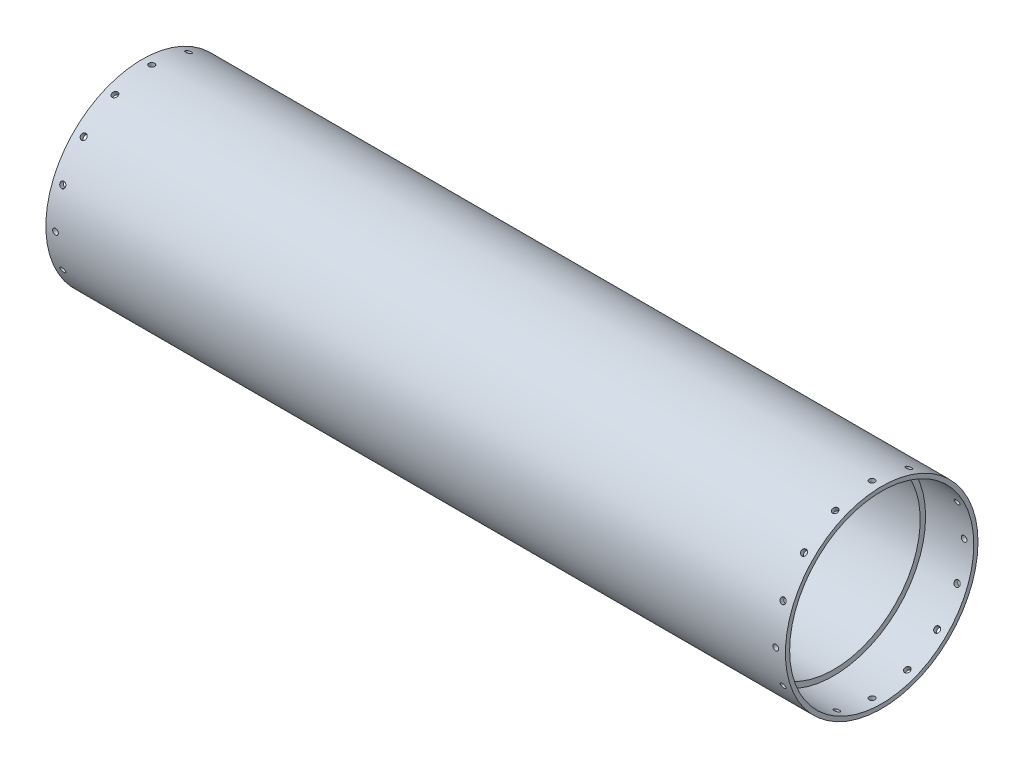
SolidWorks part; units mm, degrees
material "6061 Alloy"
ref_plane "Front Plane" through (0, 0, 0) normal (0, 0, 1) x (1, 0, 0)
ref_plane "Top Plane" through (0, 0, 0) normal (0, 1, 0) x (1, 0, 0)
ref_plane "Right Plane" through (0, 0, 0) normal (1, 0, 0) x (0, 0, -1)
sketch "Sketch1" plane through (0, 0, 0) normal (1, 0, 0) x (0, 0, -1)
  circle A0 centre (0, 0) radius 63.5
  circle A1 centre (0, 0) radius 57.15
  dimension "D1" = 127
  dimension "D2" = 6.35
extrude "Boss-Extrude1" add sketch "Sketch1" along normal blind 487.68
hole_wizard "#6 Clearance Hole1" positions "3DSketch2" profile "Sketch4" hole size "#6" standard "ANSI Inch"
sketch3d "3DSketch2"
  line L2 (6.35, 63.5, 0) -> (0, 63.5, 0) construction
  line L4 (0, 0, 0) -> (0, 63.5, 0) construction
  line L6 (6.35, 63.5, 0) -> (481.33, 63.5, 0) construction
  circle A0 centre (0, 0, 0) radius 63.5 construction
  point P0 (6.35, 63.5, 0)
  point P2 (481.33, 63.5, 0)
  point P13 (63.5, 0, 0)
  dimension "D2" = 6.35
  dimension "D1" = 6.35
sketch "Sketch4" plane through (6.35, 63.5, 0) normal (1, 0, 0) x (0, 0, 1)
  line L0 (0, 0) -> (0, 6.35)
  line L1 (0, 6.35) -> (1.8986, 6.35)
  line L2 (1.8986, 6.35) -> (1.8986, 0)
  line L5 (1.8986, 0) -> (0, 0)
  line L11 (0, -6.35) -> (0, 107.95) construction
  dimension "Thru Hole Dia." = 3.7973
  dimension "Thru Hole Depth" = 6.35
pattern_circular "CirPattern1" count 16 over 360 about axis through (487.68, 0, 0) along (-1, 0, 0) of "#6 Clearance Hole1"
sketch "Sketch5" plane through (487.68, 0, 0) normal (1, 0, 0) x (0, 0, -1)
  circle A0 centre (0, 0) radius 60.706
  circle A1 centre (0, 0) radius 63.5 construction
  dimension "D1" = 2.794
extrude "Cut-Extrude1" cut sketch "Sketch5" against normal blind 31.75
sketch "Sketch6" plane through (0, 0, 0) normal (-1, 0, 0) x (0, 0, 1)
  circle A0 centre (0, 0) radius 60.706
  circle A2 centre (0, 0) radius 63.5 construction
  dimension "D1" = 2.794
extrude "Cut-Extrude2" cut sketch "Sketch6" against normal blind 31.75
sketch "Sketch7" plane through (0, 0, 0) normal (0, 0, 1) x (1, 0, 0)
  line L0 (487.68, 63.5) -> (487.68, -63.5)
  line L1 (190.5, 0) -> (487.68, 0)
  line L2 (0, 63.5) -> (0, -63.5) construction
  circle A0 centre (190.5, 0) radius 5.6515
  dimension "D2" = 11.303
  dimension "D3" = 190.5
equation "\"D2@3DSketch2\"=\"D1@3DSketch2\""
